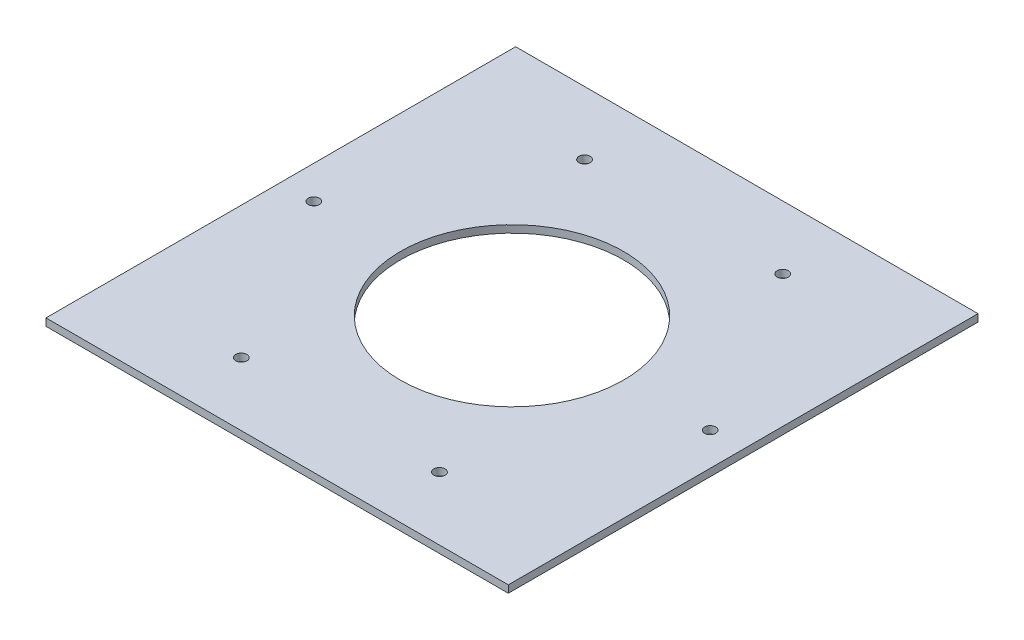
SolidWorks part; units mm, degrees
material "1350 Alloy"
ref_plane "Front Plane" through (0, 0, 0) normal (0, 0, 1) x (1, 0, 0)
ref_plane "Top Plane" through (0, 0, 0) normal (0, 1, 0) x (1, 0, 0)
ref_plane "Right Plane" through (0, 0, 0) normal (1, 0, 0) x (0, 0, -1)
sketch "Sketch1" plane through (0, 0, 0) normal (0, 1, 0) x (1, 0, 0)
  line L0 (0, 0) -> (42.8625, 74.24) construction
  line L1 (-100.0125, 101.6) -> (100.0125, 101.6)
  line L2 (-100.0125, 101.6) -> (-100.0125, -101.6)
  line L3 (-100.0125, -101.6) -> (100.0125, -101.6)
  line L4 (100.0125, 101.6) -> (100.0125, -101.6)
  line L5 (-100.0125, 101.6) -> (100.0125, -101.6) construction
  line L6 (-100.0125, -101.6) -> (100.0125, 101.6) construction
  line L7 (0, 0) -> (85.725, 0) construction
  line L8 (0, 0) -> (74.24, 42.8625) construction
  line L9 (0, 0) -> (85.725, 0) construction
  line L10 (0, 0) -> (74.24, -42.8625) construction
  line L11 (0, 0) -> (42.8625, -74.24) construction
  line L12 (0, 0) -> (0, -85.725) construction
  line L13 (0, 0) -> (-42.8625, -74.24) construction
  line L14 (0, 0) -> (-74.24, -42.8625) construction
  line L15 (0, 0) -> (-85.725, 0) construction
  line L16 (0, 0) -> (-74.24, 42.8625) construction
  line L17 (0, 0) -> (-42.8625, 74.24) construction
  line L18 (0, 0) -> (0, 85.725) construction
  circle A1 centre (42.8625, 74.24) radius 2.413
  circle A2 centre (74.24, 42.8625) radius 2.413 [skipped]
  circle A3 centre (85.725, 0) radius 2.413
  circle A4 centre (74.24, -42.8625) radius 2.413 [skipped]
  circle A5 centre (42.8625, -74.24) radius 2.413
  circle A6 centre (0, -85.725) radius 2.413 [skipped]
  circle A7 centre (-42.8625, -74.24) radius 2.413
  circle A8 centre (-74.24, -42.8625) radius 2.413 [skipped]
  circle A9 centre (-85.725, 0) radius 2.413
  circle A10 centre (-74.24, 42.8625) radius 2.413 [skipped]
  circle A11 centre (-42.8625, 74.24) radius 2.413
  circle A12 centre (0, 85.725) radius 2.413 [skipped]
  point P0 (0, 0)
  point P36 (0, 0)
  dimension "D6" = 4.826
  dimension "D1" = 203.2
  dimension "D2" = 200.025
  dimension "D4" = 60
  dimension "D5" = 85.725
  dimension "D7" = 12
extrude "Boss-Extrude1" add sketch "Sketch1" along normal blind 3.175
sketch "Sketch2" plane through (0, 3.175, 0) normal (0, 1, 0) x (1, 0, 0)
  line L1 (-139.7, 139.7) -> (139.7, 139.7) construction
  line L2 (-139.7, 139.7) -> (-139.7, -139.7) construction
  line L3 (-139.7, -139.7) -> (139.7, -139.7) construction
  line L4 (139.7, 139.7) -> (139.7, -139.7) construction
  line L5 (-139.7, 139.7) -> (139.7, -139.7) construction
  line L6 (-139.7, -139.7) -> (139.7, 139.7) construction
  circle A0 centre (-139.7, 139.7) radius 3.81
  circle A1 centre (-139.7, -139.7) radius 3.81
  circle A2 centre (139.7, -139.7) radius 3.81
  circle A3 centre (139.7, 139.7) radius 3.81
  point P0 (0, 0)
  dimension "D2" = 7.62
  dimension "D1" = 279.4
sketch "Sketch3" plane through (0, 3.175, 0) normal (0, 1, 0) x (1, 0, 0)
  circle A0 centre (0, 0) radius 48.26
  dimension "D1" = 96.52
extrude "Cut-Extrude1" cut sketch "Sketch3" against normal through all
